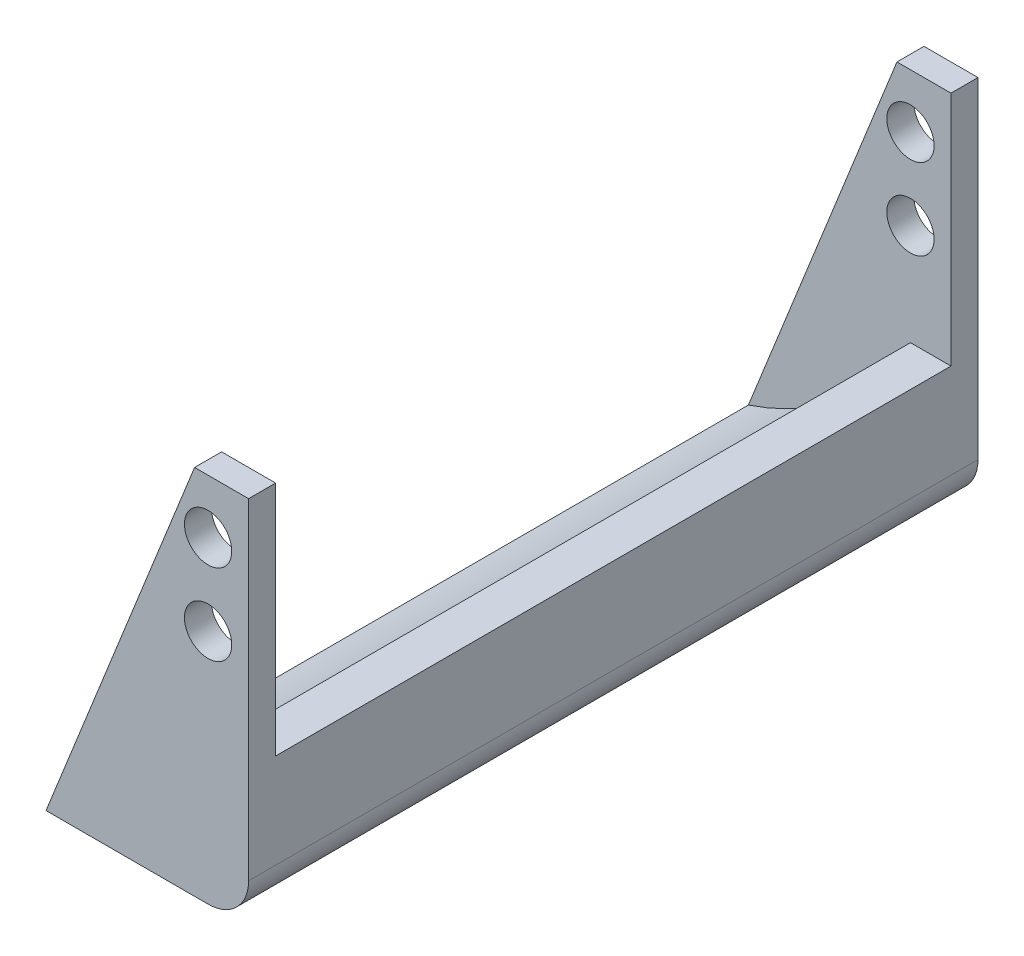
SolidWorks part; units mm, degrees
ref_plane "Front Plane" through (0, 0, 0) normal (0, 0, 1) x (1, 0, 0)
ref_plane "Top Plane" through (0, 0, 0) normal (0, 1, 0) x (1, 0, 0)
ref_plane "Right Plane" through (0, 0, 0) normal (1, 0, 0) x (0, 0, -1)
sketch "Sketch1" plane through (0, 0, 0) normal (0, 0, 1) x (1, 0, 0)
  line L0 (0, 0) -> (15, 0)
  line L1 (15, 0) -> (15, 10)
  line L2 (12, 10) -> (15, 10)
  arc A0 (0, 0) -> (12, 10) centre (-6.8237, 20.3884) ccw
  point P6 (0, 0)
  point P8 (4.6677, 4.565)
  point P9 (0, 0)
  dimension "D3" = 21.5
  dimension "D1" = 10
  dimension "D2" = 15
  dimension "D4" = 3
extrude "Boss-Extrude1" add sketch "Sketch1" along normal mid plane 50
sketch "Sketch2" plane through (0, 0, 25) normal (0, 0, 1) x (1, 0, 0)
  line L0 (15, 0) -> (15, 27.5)
  line L1 (15, 27.5) -> (11, 27.5)
  line L2 (11, 27.5) -> (0, 0)
  line L3 (0, 0) -> (15, 0)
  line L4 (12, 27.5) -> (12, 23.5) construction
  line L5 (12, 23.5) -> (12, 17.5) construction
  circle A0 centre (12, 23.5) radius 1.75
  circle A1 centre (12, 17.5) radius 1.75
  dimension "D5" = 3.5
  dimension "D1" = 27.5
  dimension "D2" = 4
  dimension "D3" = 4
  dimension "D4" = 6
  dimension "D6" = 3
extrude "Boss-Extrude2" add sketch "Sketch2" along normal blind 2
mirror "Mirror1" about plane through (0, 0, 0) normal (0, 0, 1) of "Boss-Extrude2"
fillet "Fillet1" radius 3 1 edges at (15, 0, 0)
